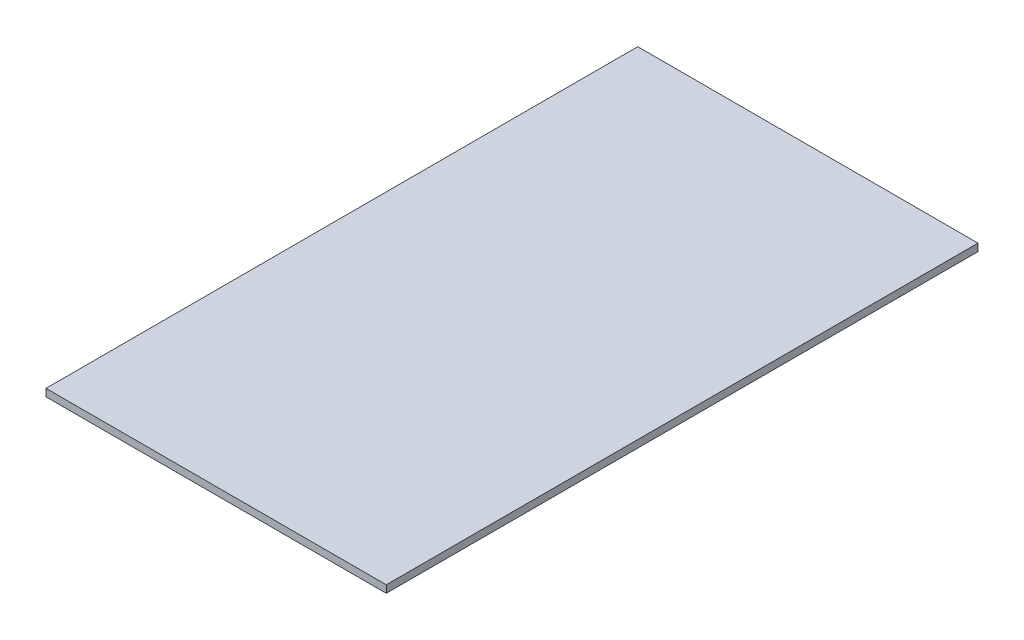
SolidWorks part; units mm, degrees
ref_plane "Front Plane" through (0, 0, 0) normal (0, 0, 1) x (1, 0, 0)
ref_plane "Top Plane" through (0, 0, 0) normal (0, 1, 0) x (1, 0, 0)
ref_plane "Right Plane" through (0, 0, 0) normal (1, 0, 0) x (0, 0, -1)
sketch "Sketch1" plane through (0, 0, 0) normal (0, 1, 0) x (1, 0, 0)
  line L0 (0.9272, 231.0049) -> (293.0272, 231.0049) construction
  line L1 (0.9272, -22.9951) -> (293.0272, -22.9951)
  line L2 (0.9272, -22.9951) -> (0.9272, 485.0049)
  line L3 (0.9272, 485.0049) -> (293.0272, 485.0049)
  line L4 (293.0272, -22.9951) -> (293.0272, 485.0049)
  line L5 (293.0272, 231.0049) -> (146.9772, 485.0049) construction
  line L6 (146.9772, 485.0049) -> (0.9272, 231.0049) construction
  dimension "D1" = 508
  dimension "D2" = 292.1
extrude "Boss-Extrude1" add sketch "Sketch1" along normal blind 6.35 contours L2 L3 L4 L1
